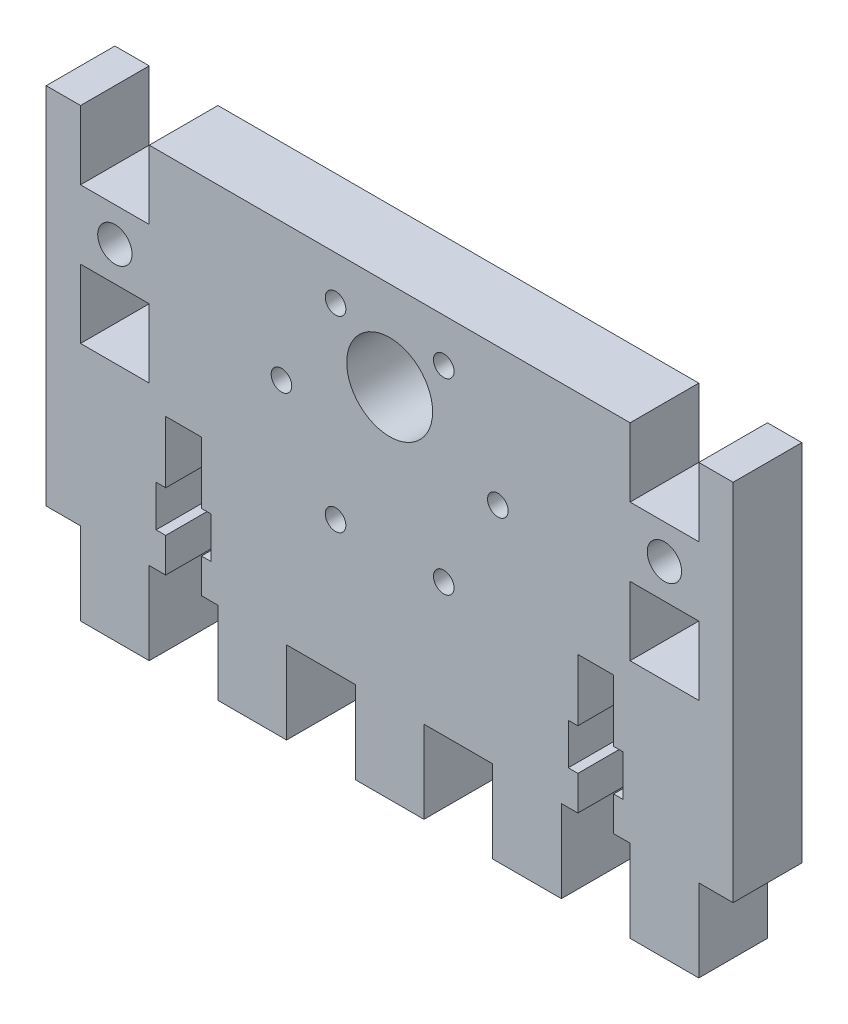
SolidWorks part; units mm, degrees
material "Acrylic (Medium-high impact)"
ref_plane "Front Plane" through (0, 0, 0) normal (0, 0, 1) x (1, 0, 0)
ref_plane "Top Plane" through (0, 0, 0) normal (0, 1, 0) x (1, 0, 0)
ref_plane "Right Plane" through (0, 0, 0) normal (1, 0, 0) x (0, 0, -1)
sketch "Sketch1" plane through (0, 0, 0) normal (0, 0, 1) x (1, 0, 0)
  line L1 (50, 32.5) -> (-50, 32.5)
  line L2 (50, 32.5) -> (50, -32.5)
  line L3 (50, -32.5) -> (-50, -32.5)
  line L4 (-50, 32.5) -> (-50, -32.5)
  line L5 (50, 32.5) -> (-50, -32.5) construction
  line L6 (50, -32.5) -> (-50, 32.5) construction
  point P0 (0, 0)
  dimension "D1" = 100
  dimension "D3" = 65
extrude "Boss-Extrude1" add sketch "Sketch1" along normal blind 10
sketch "Sketch2" plane through (0, 0, 10) normal (0, 0, 1) x (1, 0, 0)
  line L1 (0, 12.5) -> (-15.75, 12.5) construction
  line L2 (50, 32.5) -> (-50, 32.5) construction
  circle A0 centre (-15.75, 12.5) radius 1.5
  circle A1 centre (-7.875, 26.1399) radius 1.5
  circle A2 centre (7.875, 26.1399) radius 1.5
  circle A3 centre (15.75, 12.5) radius 1.5
  circle A4 centre (7.875, -1.1399) radius 1.5
  circle A5 centre (-7.875, -1.1399) radius 1.5
  circle A6 centre (0, 19.5) radius 6.25
  dimension "D2" = 3
  dimension "D6" = 7
  dimension "D3" = 12.5
  dimension "D5" = 15.75
  dimension "D7" = 20
  dimension "D4" = 6
extrude "Cut-Extrude1" cut sketch "Sketch2" against normal through all
sketch "Sketch3" plane through (0, 0, 10) normal (0, 0, 1) x (1, 0, 0)
  line L0 (50, -32.5) -> (-50, -32.5) construction
  line L1 (-35, -32.5) -> (-25, -32.5)
  line L2 (-35, -32.5) -> (-35, -20.5)
  line L3 (-35, -20.5) -> (-25, -20.5)
  line L4 (-25, -32.5) -> (-25, -20.5)
  line L5 (-50, 32.5) -> (-50, -32.5) construction
  dimension "D1" = 15
  dimension "D2" = 10
  dimension "D3" = 12
extrude "Cut-Extrude2" cut sketch "Sketch3" against normal through all
pattern_linear "LPattern1" count 4 spacing 20 along (1, 0, 0) of "Cut-Extrude2"
sketch "Sketch4" plane through (0, 0, 10) normal (0, 0, 1) x (1, 0, 0)
  line L0 (-25, -20.5) -> (-35, -20.5) construction
  line L1 (-32.6, -20.5) -> (-27.4, -20.5)
  line L2 (-32.6, -20.5) -> (-32.6, -15.5)
  line L3 (-32.6, -0.5) -> (-27.4, -0.5)
  line L4 (-27.4, -20.5) -> (-27.4, -15.5)
  line L5 (-25, -32.5) -> (-25, -20.5) construction
  line L6 (-34, -9.5) -> (-32.6, -9.5)
  line L7 (-34, -9.5) -> (-34, -15.5)
  line L8 (-34, -15.5) -> (-32.6, -15.5)
  line L9 (-26, -9.5) -> (-26, -15.5)
  line L10 (-27.4, -9.5) -> (-26, -9.5)
  line L11 (-27.4, -9.5) -> (-27.4, -0.5)
  line L12 (-27.4, -15.5) -> (-26, -15.5)
  line L13 (-32.6, -9.5) -> (-32.6, -0.5)
  line L15 (-50, -32.5) -> (-45, -32.5)
  line L16 (-50, -32.5) -> (-50, -20.5)
  line L17 (-50, -20.5) -> (-45, -20.5)
  line L18 (-45, -32.5) -> (-45, -20.5)
  line M13 (-50, 32.5) -> (-50, -32.5)
  line M14 (-50, -32.5) -> (-35, -32.5)
  dimension "D1" = 20
  dimension "D2" = 5.2
  dimension "D3" = 5
  dimension "D4" = 6
  dimension "D5" = 8
  dimension "D6" = 1.4
  dimension "D7" = 1
  dimension "D8" = 5
extrude "Cut-Extrude3" cut sketch "Sketch4" against normal through all contours L18 L17 M14 M13 | L7 L8 L2 L1 L4 L12 L9 L10 L11 L3 L13 L6
sketch "Sketch6" plane through (0, 0, 10) normal (0, 0, 1) x (1, 0, 0)
  line L1 (-45, 32.5) -> (-35, 32.5)
  line L2 (-45, 32.5) -> (-45, 22.5)
  line L3 (-45, 22.5) -> (-35, 22.5)
  line L4 (-35, 32.5) -> (-35, 22.5)
  line L5 (-45, 12.5) -> (-35, 12.5)
  line L6 (-45, 12.5) -> (-45, 2.5)
  line L7 (-45, 2.5) -> (-35, 2.5)
  line L8 (-35, 12.5) -> (-35, 2.5)
  line L9 (50, 32.5) -> (-50, 32.5) construction
  line L10 (-50, 32.5) -> (-50, -20.5) construction
  circle A0 centre (-40, 17.5) radius 2.5
  point P9 (-35, 7.5)
  dimension "D6" = 5
  dimension "D1" = 10
  dimension "D2" = 10
  dimension "D3" = 10
  dimension "D4" = 10
  dimension "D5" = 5
  dimension "D7" = 5
  dimension "D8" = 5
extrude "Cut-Extrude4" cut sketch "Sketch6" against normal through all
mirror "Mirror1" about plane through (0, 0, 0) normal (1, 0, 0) of "Cut-Extrude4", "Cut-Extrude3"
